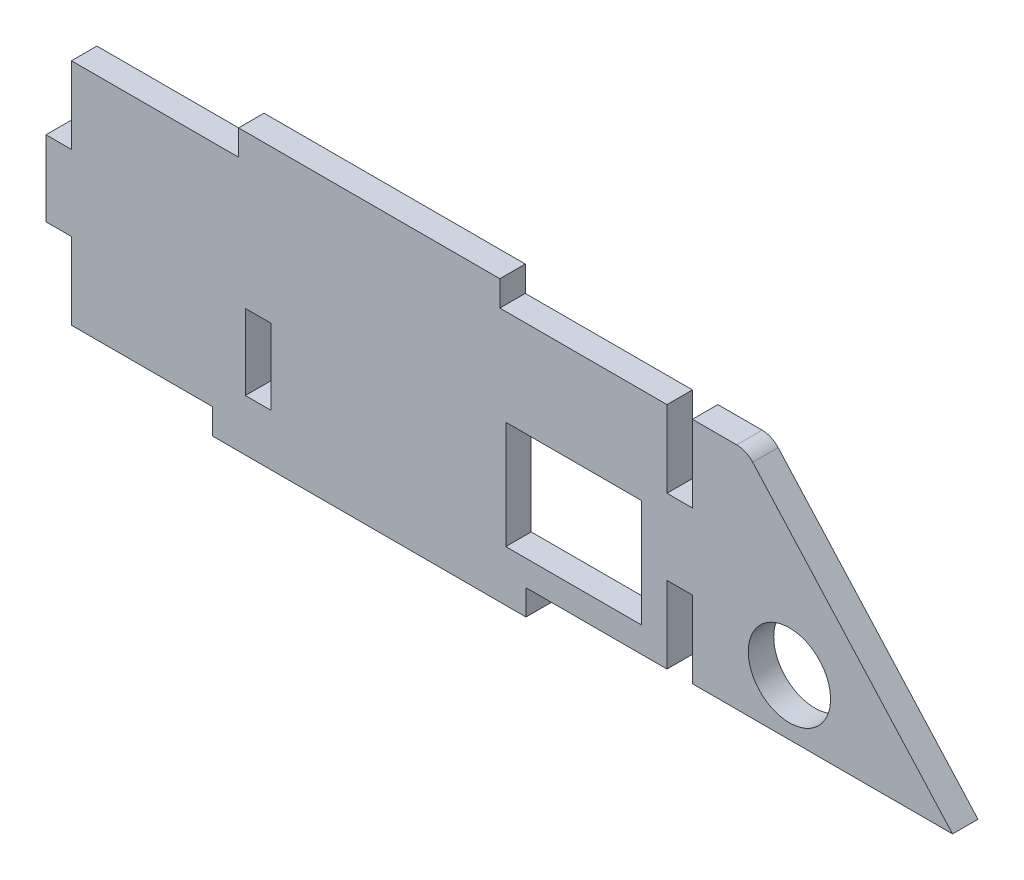
SolidWorks part; units mm, degrees
material "Acrylic (Medium-high impact)"
ref_plane "Front Plane" through (0, 0, 0) normal (0, 0, 1) x (1, 0, 0)
ref_plane "Top Plane" through (0, 0, 0) normal (0, 1, 0) x (1, 0, 0)
ref_plane "Right Plane" through (0, 0, 0) normal (1, 0, 0) x (0, 0, -1)
sketch "스케치1" plane through (0, 0, 0) normal (0, 0, 1) x (1, 0, 0)
  line L0 (0, -10.0061) -> (0, 0) construction
  line L1 (-38.1, -15) -> (38.1, -15)
  line L2 (-38.1, -15) -> (-38.1, 15)
  line L3 (-38.1, 15) -> (38.1, 15)
  line L4 (38.1, -15) -> (38.1, 15)
  line L5 (-38.1, -15) -> (38.1, 15) construction
  line L6 (-38.1, 15) -> (38.1, -15) construction
  line L7 (-26.5684, -12) -> (26.5684, -12) construction
  line L8 (-26.5684, -12) -> (-26.5684, -8.0122) construction
  line L9 (-26.5684, -8.0122) -> (26.5684, -8.0122) construction
  line L10 (26.5684, -12) -> (26.5684, -8.0122) construction
  line L11 (-26.5684, -12) -> (26.5684, -8.0122) construction
  line L12 (-26.5684, -8.0122) -> (26.5684, -12) construction
  line L14 (13.9573, -8.0122) -> (22.8981, -8.0122) construction
  line L15 (13.9573, -8.0122) -> (13.9573, 3.0876) construction
  line L16 (13.9573, 3.0876) -> (22.8981, 3.0876) construction
  line L17 (22.8981, -8.0122) -> (22.8981, 3.0876) construction
  line L18 (13.9573, -8.0122) -> (22.8981, 3.0876) construction
  line L19 (13.9573, 3.0876) -> (22.8981, -8.0122) construction
  line L20 (-17.5641, -8.0122) -> (-5.4102, -8.0122) construction
  line L21 (-17.5641, -8.0122) -> (-17.5641, 2.732) construction
  line L22 (-17.5641, 2.732) -> (-5.4102, 2.732) construction
  line L23 (-5.4102, -8.0122) -> (-5.4102, 2.732) construction
  line L24 (-17.5641, -8.0122) -> (-5.4102, 2.732) construction
  line L25 (-17.5641, 2.732) -> (-5.4102, -8.0122) construction
  point P0 (0, 0)
  point P6 (0, -10.0061)
  point P17 (18.4277, -2.4623)
  point P22 (-11.4872, -2.6401)
  dimension "D1" = 76.2
  dimension "D2" = 53.1368
  dimension "D3" = 3.9878
  dimension "D4" = 3
  dimension "D5" = 8.9408
  dimension "D6" = 30
  dimension "D7" = 11.0998
  dimension "D8" = 10.7442
  dimension "D9" = 12.1539
  dimension "D10" = 19.3675
  dimension "D11" = 9.0043
extrude "보스-돌출1" add sketch "스케치1" along normal blind 3
sketch "스케치2" plane through (0, 0, 3) normal (0, 0, 1) x (1, 0, 0)
  line L0 (-38.1, -15) -> (38.1, -15) construction
  line L1 (-38.1, -15) -> (-18.4785, -15)
  line L2 (-38.1, -15) -> (-38.1, -12)
  line L3 (-38.1, -12) -> (-18.4785, -12)
  line L4 (-18.4785, -15) -> (-18.4785, -12)
  line L5 (-38.1, -15) -> (-18.4785, -12) construction
  line L6 (-38.1, -12) -> (-18.4785, -15) construction
  line L7 (18.4785, -15) -> (38.1, -15)
  line L8 (18.4785, -15) -> (18.4785, -12)
  line L9 (18.4785, -12) -> (38.1, -12)
  line L10 (38.1, -15) -> (38.1, -12)
  line L11 (18.4785, -15) -> (38.1, -12) construction
  line L12 (18.4785, -12) -> (38.1, -15) construction
  line L13 (38.1, -15) -> (38.1, 15) construction
  line L14 (18.4785, -12) -> (-18.4785, -12) construction
  point P4 (-28.2892, -13.5)
  point P10 (28.2892, -13.5)
  dimension "D1" = 36.957
  dimension "D2" = 3
extrude "컷-돌출1" cut sketch "스케치2" against normal up to surface (3 mm away) up to face at (0, 0, 0)
sketch "스케치3" plane through (0, 0, 3) normal (0, 0, 1) x (1, 0, 0)
  line L0 (-38.1, 15) -> (-38.1, -12) construction
  line L1 (-38.1, -2.945) -> (-35.1, -2.945) construction
  line L2 (-38.1, -2.945) -> (-38.1, 5.945) construction
  line L3 (-38.1, 5.945) -> (-35.1, 5.945) construction
  line L4 (-35.1, -2.945) -> (-35.1, 5.945) construction
  line L5 (-38.1, -2.945) -> (-35.1, 5.945) construction
  line L6 (-38.1, 5.945) -> (-35.1, -2.945) construction
  line L7 (38.1, -12) -> (38.1, 15) construction
  line L8 (38.1, 5.945) -> (35.1, 5.945) construction
  line L9 (38.1, 5.945) -> (38.1, -2.945) construction
  line L10 (38.1, -2.945) -> (35.1, -2.945) construction
  line L11 (35.1, 5.945) -> (35.1, -2.945) construction
  line L12 (38.1, 5.945) -> (35.1, -2.945) construction
  line L13 (38.1, -2.945) -> (35.1, 5.945) construction
  line L14 (38.1, 1.5) -> (-38.1, 1.5) construction
  line L16 (-35.1, 5.945) -> (-38.1, 5.945)
  line L17 (-35.1, 5.945) -> (-35.1, 15)
  line L18 (-35.1, 15) -> (-38.1, 15)
  line L19 (-38.1, 5.945) -> (-38.1, 15)
  line L20 (-35.1, 5.945) -> (-38.1, 15) construction
  line L21 (-35.1, 15) -> (-38.1, 5.945) construction
  line L22 (-35.1, -2.945) -> (-38.1, -2.945)
  line L23 (-35.1, -2.945) -> (-35.1, -12)
  line L24 (-35.1, -12) -> (-38.1, -12)
  line L25 (-38.1, -2.945) -> (-38.1, -12)
  line L26 (-35.1, -2.945) -> (-38.1, -12) construction
  line L27 (-35.1, -12) -> (-38.1, -2.945) construction
  line L28 (35.1, 5.945) -> (38.1, 5.945)
  line L29 (35.1, 5.945) -> (35.1, 15)
  line L30 (35.1, 15) -> (38.1, 15)
  line L31 (38.1, 5.945) -> (38.1, 15)
  line L32 (35.1, 5.945) -> (38.1, 15) construction
  line L33 (35.1, 15) -> (38.1, 5.945) construction
  line L34 (35.1, -2.945) -> (38.1, -2.945)
  line L35 (35.1, -2.945) -> (35.1, -12)
  line L36 (35.1, -12) -> (38.1, -12)
  line L37 (38.1, -2.945) -> (38.1, -12)
  line L38 (35.1, -2.945) -> (38.1, -12) construction
  line L39 (35.1, -12) -> (38.1, -2.945) construction
  point P4 (-36.6, 1.5)
  point P11 (36.6, 1.5)
  point P18 (-36.6, 10.4725)
  point P22 (-36.6, -7.4725)
  point P26 (36.6, 10.4725)
  point P30 (36.6, -7.4725)
  dimension "D1" = 8.89
  dimension "D2" = 3
extrude "컷-돌출2" cut sketch "스케치3" against normal up to surface (3 mm away) up to face at (0, -6, 0)
sketch "스케치5" plane through (0, 0, 3) normal (0, 0, 1) x (1, 0, 0)
  line L0 (44.45, 15) -> (35.1, 15) construction
  line L1 (44.45, 15) -> (68.7609, 15) construction
  line L2 (44.45, 15) -> (44.45, -12) construction
  line L3 (44.45, -12) -> (68.7609, -12)
  line L4 (68.7609, 15) -> (68.7609, -12) construction
  line L5 (44.45, 15) -> (68.7609, -12)
  line L6 (44.45, -12) -> (68.7609, 15) construction
  line L7 (35.1, -12) -> (44.45, -12) construction
  line L8 (-44.45, -18.543) -> (44.45, -18.543) construction
  line L9 (38.1, 15) -> (44.45, 15)
  line L10 (38.1, 15) -> (38.1, -12)
  line L11 (38.1, -12) -> (44.45, -12)
  line L13 (38.1, 15) -> (44.45, -12) construction
  line L14 (38.1, -12) -> (44.45, 15) construction
  line L15 (0, 0) -> (0, -18.543) construction
  line L16 (44.45, -18.543) -> (44.45, -12) construction
  point P4 (56.6055, 1.5)
  point P13 (41.275, 1.5)
  dimension "D1" = 48
  dimension "D2" = 27
  dimension "D3" = 88.9
  dimension "D4" = 18.543
extrude "보스-돌출2" add sketch "스케치5" against normal blind 3
sketch "스케치6" plane through (0, 0, 3) normal (0, 0, 1) x (1, 0, 0)
  line L0 (0, 0) -> (0, 16.5) construction
  line L1 (35.1, 15) -> (-35.1, 15) construction
  line L2 (-15.3988, 18) -> (15.3987, 18)
  line L3 (-15.3988, 18) -> (-15.3988, 15)
  line L4 (-15.3988, 15) -> (15.3987, 15)
  line L5 (15.3987, 18) -> (15.3987, 15)
  line L6 (-15.3988, 18) -> (15.3987, 15) construction
  line L7 (-15.3988, 15) -> (15.3987, 18) construction
  dimension "D1" = 30.7975
  dimension "D2" = 3
extrude "보스-돌출3" add sketch "스케치6" against normal up to surface (3 mm away) up to face at (9.4705, -1.5, 0)
sketch "스케치7" plane through (0, 0, 0) normal (0, 0, -1) x (-1, 0, 0)
  line L0 (-35.1, -2.945) -> (-35.1, -12) construction
  line L1 (-32.1, 3.7) -> (-16.098, 3.7)
  line L2 (-32.1, 3.7) -> (-32.1, -9)
  line L3 (-32.1, -9) -> (-16.098, -9)
  line L4 (-16.098, 3.7) -> (-16.098, -9)
  line L5 (-32.1, 3.7) -> (-16.098, -9) construction
  line L6 (-32.1, -9) -> (-16.098, 3.7) construction
  line L7 (-35.284, -10.651) -> (-12.914, -10.651) construction
  line L8 (-35.284, -10.651) -> (-35.284, 5.351) construction
  line L9 (-35.284, 5.351) -> (-12.914, 5.351) construction
  line L10 (-12.914, -10.651) -> (-12.914, 5.351) construction
  line L11 (-35.284, -10.651) -> (-12.914, 5.351) construction
  line L12 (-35.284, 5.351) -> (-12.914, -10.651) construction
  line L13 (-35.1, -12) -> (-18.4785, -12) construction
  point P0 (-24.099, -2.65)
  point P8 (-24.099, -2.65)
  dimension "D1" = 12.7
  dimension "D2" = 16.002
  dimension "D3" = 16.002
  dimension "D4" = 3
  dimension "D5" = 3
extrude "컷-돌출3" cut sketch "스케치7" against normal up to surface (3 mm away) up to face at (7.8921, 1.5, 3)
sketch "스케치8" plane through (0, 0, 0) normal (0, 0, -1) x (-1, 0, 0)
  line L1 (-38.1, -12) -> (-68.7609, -12) construction
  line L2 (-57.15, -12) -> (-41.91, -12) construction
  line L3 (-49.53, -5.42) -> (-49.53, -12) construction
  line L4 (-38.1, -2.945) -> (-38.1, -12) construction
  circle A0 centre (-49.53, -5.42) radius 4.85
  point P4 (-47.7627, -1.84)
  point P9 (-49.53, -0.57)
  dimension "D1" = 10.16
  dimension "D3" = 9.7
  dimension "D2" = 15.24
  dimension "D4" = 11.43
  dimension "D5" = 11.43
extrude "컷-돌출4" cut sketch "스케치8" against normal up to surface (3 mm away) up to face at (24.099, -2.65, 3)
fillet "필렛1" radius 2.54 1 edges at (44.45, 15, 1.5)
sketch "스케치9" plane through (0, 0, 0) normal (0, 0, -1) x (-1, 0, 0)
  line L0 (35.1, -12) -> (35.1, -2.945) construction
  line L1 (11.6, -8.9252) -> (14.6, -8.9252)
  line L2 (11.6, -8.9252) -> (11.6, -0.0352)
  line L3 (11.6, -0.0352) -> (14.6, -0.0352)
  line L4 (14.6, -8.9252) -> (14.6, -0.0352)
  line L5 (11.6, -8.9252) -> (14.6, -0.0352) construction
  line L6 (11.6, -0.0352) -> (14.6, -8.9252) construction
  line L7 (18.4785, -12) -> (18.4785, 3.0396) construction
  line L8 (18.4785, -4.4802) -> (13.1, -4.4802) construction
  point P0 (13.1, -4.4802)
  dimension "D1" = 20.5
  dimension "D2" = 3
  dimension "D3" = 8.89
  dimension "D4" = 15.0396
extrude "컷-돌출5" cut sketch "스케치9" against normal up to surface (3 mm away) up to face at (44.68, -5.42, 3)
